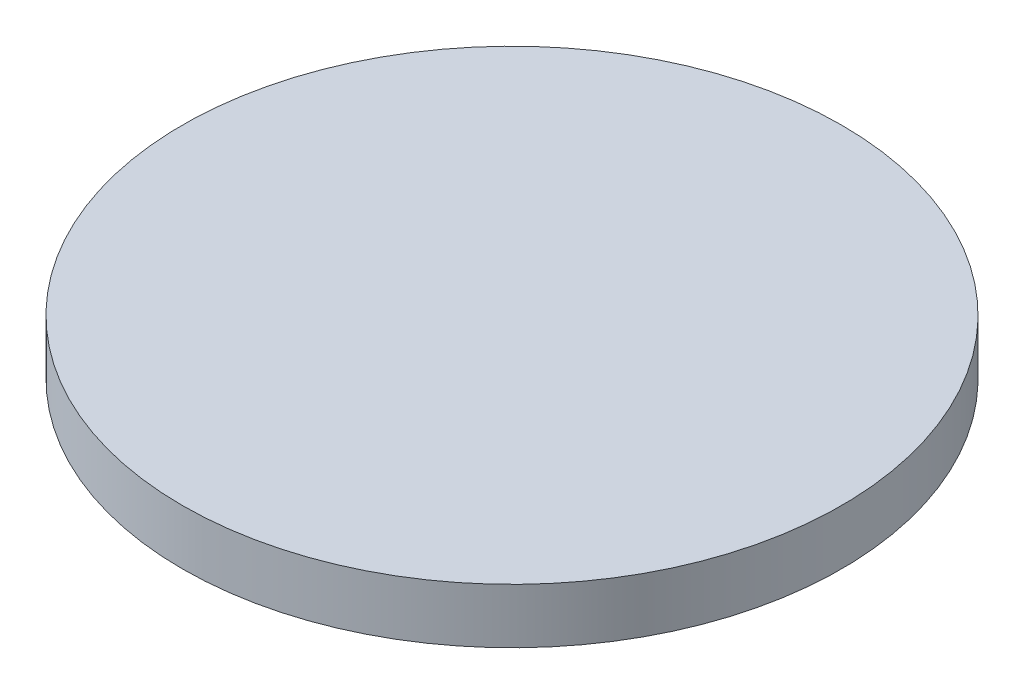
SolidWorks part; units mm, degrees
ref_plane "Front Plane" through (0, 0, 0) normal (0, 0, 1) x (1, 0, 0)
ref_plane "Top Plane" through (0, 0, 0) normal (0, 1, 0) x (1, 0, 0)
ref_plane "Right Plane" through (0, 0, 0) normal (1, 0, 0) x (0, 0, -1)
sketch "Sketch1" plane through (0, 0, 0) normal (0, 1, 0) x (1, 0, 0)
  circle A0 centre (0, 0) radius 30
  dimension "D1" = 60
extrude "Boss-Extrude1" add sketch "Sketch1" along normal blind 5
sketch "Sketch2" plane through (0, 0, 0) normal (0, -1, 0) x (1, 0, 0)
  line L0 (-3.0404, -5.2883) -> (3.0652, -16.9092)
  line L1 (7.9796, -15.2198) -> (5.6493, -2.3011)
  line L2 (3.0404, 5.2883) -> (-3.0652, 16.9092)
  line L3 (-7.9796, 15.2198) -> (-5.6493, 2.3011)
  line L4 (-2.9654, -5.216) -> (3.1522, -16.8597)
  line L5 (-7.8806, 15.2342) -> (-5.5457, 2.2901)
  line L6 (2.9654, 5.216) -> (-3.1522, 16.8597)
  line L7 (7.8806, -15.2342) -> (5.5457, -2.2901)
  line L8 (-2.9654, -5.216) -> (3.1522, -16.8597) construction
  line L9 (-7.8806, 15.2342) -> (-5.5457, 2.2901) construction
  line L10 (2.9654, 5.216) -> (-3.1522, 16.8597) construction
  line L11 (7.8806, -15.2342) -> (5.5457, -2.2901) construction
  arc A0 (3.0652, -16.9092) -> (7.9796, -15.2198) centre (5.3335, -15.515) ccw
  arc A1 (5.6493, -2.3011) -> (3.0404, 5.2883) centre (0, 0) ccw
  arc A2 (-3.0652, 16.9092) -> (-7.9796, 15.2198) centre (-5.3335, 15.515) ccw
  arc A3 (-5.6493, 2.3011) -> (-3.0404, -5.2883) centre (0, 0) ccw
  arc A4 (-5.5457, 2.2901) -> (-2.9654, -5.216) centre (0, 0) ccw
  arc A5 (-3.1522, 16.8597) -> (-7.8806, 15.2342) centre (-5.3335, 15.515) ccw
  arc A6 (5.5457, -2.2901) -> (2.9654, 5.216) centre (0, 0) ccw
  arc A7 (3.1522, -16.8597) -> (7.8806, -15.2342) centre (5.3335, -15.515) ccw
  arc A8 (-5.5457, 2.2901) -> (-2.9654, -5.216) centre (0, 0) ccw construction
  arc A9 (-3.1522, 16.8597) -> (-7.8806, 15.2342) centre (-5.3335, 15.515) ccw construction
  arc A10 (5.5457, -2.2901) -> (2.9654, 5.216) centre (0, 0) ccw construction
  arc A11 (3.1522, -16.8597) -> (7.8806, -15.2342) centre (5.3335, -15.515) ccw construction
  dimension "D1" = 0
  dimension "D2" = 0.1
extrude "Cut-Extrude1" cut sketch "Sketch2" against normal blind 2.5
